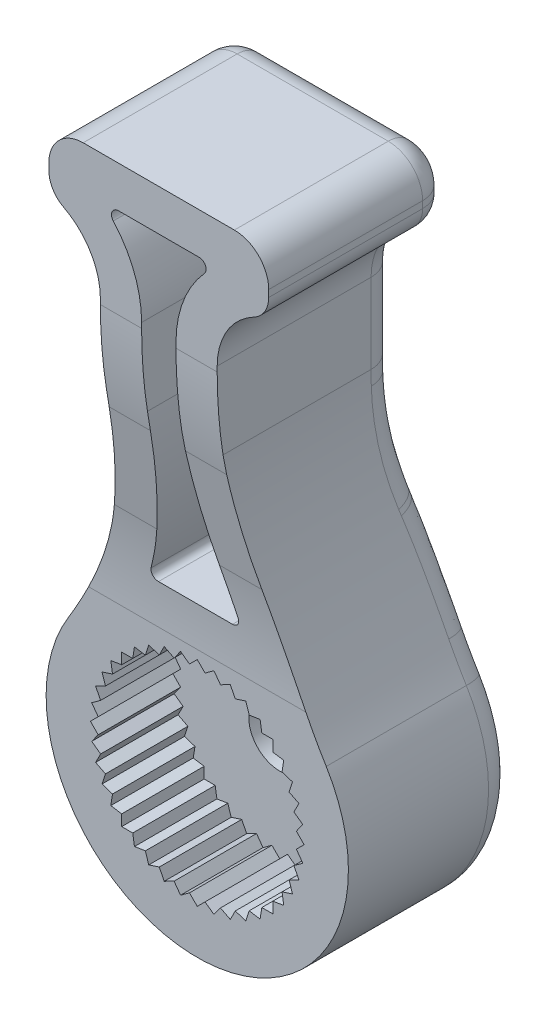
SolidWorks part; units mm, degrees
ref_plane "Plan de face" through (0, 0, 0) normal (0, 0, 1) x (1, 0, 0)
ref_plane "Plan de dessus" through (0, 0, 0) normal (0, 1, 0) x (1, 0, 0)
ref_plane "Plan de droite" through (0, 0, 0) normal (1, 0, 0) x (0, 0, -1)
sketch "Esquisse1" plane through (0, 0, 0) normal (0, 0, 1) x (1, 0, 0)
  line L0 (-5.5, 39) -> (5.5, 39)
  line L1 (0, 0) -> (0, 54.3296) construction
  line L2 (4.25, 29.8002) -> (4.25, 23.9883)
  line L3 (0, 0) -> (0, -12.9664) construction
  line L4 (-8, 36.5) -> (-8, 36)
  line L5 (8, 36.5) -> (8, 36)
  line L6 (-4.25, 29.8002) -> (-4.25, 23.9883)
  arc A0 (-9.3859, 5.7363) -> (9.3859, 5.7363) centre (0, 0) ccw
  arc A1 (5.5, 39) -> (8, 36.5) centre (5.5, 36.5) cw
  arc A2 (9.3859, 5.7363) -> (4.25, 23.9883) centre (39.25, 23.9883) cw
  arc A3 (-6.9286, 34.2286) -> (-4.25, 29.8002) centre (-9.25, 29.8002) cw
  arc A4 (6.9286, 34.2286) -> (8, 36) centre (6, 36) ccw
  arc A5 (6.9286, 34.2286) -> (4.25, 29.8002) centre (9.25, 29.8002) ccw
  arc A6 (-6.9286, 34.2286) -> (-8, 36) centre (-6, 36) cw
  arc A7 (-9.3859, 5.7363) -> (-4.25, 23.9883) centre (-39.25, 23.9883) ccw
  arc A8 (-5.5, 39) -> (-8, 36.5) centre (-5.5, 36.5) ccw
  point P12 (8, 39)
  point P13 (0, 39)
  point P15 (-8, 39)
  dimension "D1" = 22
  dimension "D7" = 2.5
  dimension "D8" = 4.7714
  dimension "D9" = 5
  dimension "D6" = 2
  dimension "D10" = 35
  dimension "D2" = 39
  dimension "D3" = 8.5
  dimension "D5" = 8
extrude "Boss.-Extru.1" add sketch "Esquisse1" along normal blind 15
sketch "Esquisse2" plane through (0, 0, 0) normal (1, 0, 0) x (0, 0, -1)
  line L0 (-1.8, 39) -> (-1.8, 22.8889)
  line L1 (-12.2, -12.1591) -> (-12.2, 8.4134)
  line L2 (0, -11) -> (0, 5.7363) construction
  line L3 (-15, 34.2286) -> (-15, 29.8002) construction
  line L4 (-15, 39) -> (0, 39) construction
  line L5 (-1.8, 39) -> (0, 39)
  line L6 (-0.9463, 15.206) -> (-0.8537, 14.794)
  line L7 (0, 5.7363) -> (0, 23.9883) construction
  line L8 (0, 5.7363) -> (0, 7.1111)
  line L9 (-15, 23.9883) -> (-15, 29.8002) construction
  line L10 (-15, 29.4275) -> (-15, 29.8002)
  line L11 (-15, 23.9883) -> (-15, 5.7363) construction
  line L12 (-12.8649, 15.2032) -> (-14.3351, 22.6376)
  line L13 (-15, 29.8002) -> (-17.0161, 29.8002)
  line L14 (-17.0161, 29.8002) -> (-17.0161, -12.1591)
  line L15 (-17.0161, -12.1591) -> (-12.2, -12.1591)
  line L16 (0, 39) -> (7.2396, 39)
  line L17 (7.2396, 39) -> (7.2396, 8.4134)
  line L18 (7.2396, 8.4134) -> (0, 5.7363)
  arc A0 (-0.8537, 14.794) -> (0, 7.1111) centre (-35, 7.1111) cw
  arc A1 (-1.8, 22.8889) -> (-0.9463, 15.206) centre (33.2, 22.8889) ccw
  arc A2 (-15, 29.4275) -> (-14.3351, 22.6376) centre (20, 29.4275) ccw
  arc A3 (-12.2, 8.4134) -> (-12.8649, 15.2032) centre (-47.2, 8.4134) ccw
  point P16 (0, 11)
  point P19 (-1.8, 19)
  point P27 (-15, 26)
  point P30 (-12.2, 11.8409)
  dimension "D5" = 35
  dimension "D8" = 35
  dimension "D1" = 12.2
  dimension "D2" = 13.2
  dimension "D3" = 20
  dimension "D4" = 11
  dimension "D6" = 24
  dimension "D7" = 13
extrude "Enlèv. mat.-Extru.1" cut sketch "Esquisse2" against normal mid plane 25
fillet "Congé1" radius 2 22 edges at (4.2543, 23.4385, 1.8) (4.25, 26.8942, 1.8) (4.9717, 32.3879, 1.8) (7.7113, 34.9649, 1.8) (8, 36.25, 1.8) (7.2678, 38.2678, 1.8) (0, 39, 1.8) (-7.2678, 38.2678, 1.8) (-8, 36.25, 1.8) (-7.7113, 34.9649, 1.8) (-4.9717, 32.3879, 1.8) (-4.25, 26.8942, 1.8) (-4.2543, 23.4385, 1.8) (4.4594, 20.165, 1.6938) (5.4239, 14.9998, 0.9) (-5.4239, 14.9998, 0.9) (8.9791, 6.4192, 0) (-8.9791, 6.4192, 0) (0, -11, 0)
sketch "Esquisse3" plane through (0, 0, 12.2) normal (0, 0, 1) x (1, 0, 0)
  line L0 (-4.5719, 6.2928) -> (-3.7792, 6.1673)
  line L1 (-5.5, -5.5) -> (-4.6964, -5.5)
  line L2 (-5.5, -5.5) -> (-5.5, -4.6973)
  line L3 (-5.5, 5.5) -> (-4.6975, 5.5)
  line L4 (5.5, -5.5) -> (5.5, -4.6966)
  line L5 (-5.5, -5.5) -> (5.5, 5.5) construction
  line L6 (-5.5, 5.5) -> (5.5, -5.5) construction
  line L7 (-6.2927, -4.5717) -> (-6.1671, -3.7789)
  line L8 (-6.2927, -4.5717) -> (-5.5, -4.6973)
  line L9 (4.5719, -6.2925) -> (4.6974, -5.5)
  line L10 (-3.5312, 6.9307) -> (-2.7679, 6.6827)
  line L11 (-6.9304, -3.5309) -> (-6.6823, -2.7675)
  line L12 (-6.9304, -3.5309) -> (-6.1671, -3.7789)
  line L13 (3.5313, -6.9301) -> (3.7792, -6.167)
  line L14 (-2.4035, 7.3979) -> (-1.6884, 7.0336)
  line L15 (-7.3974, -2.4031) -> (-7.0329, -1.6879)
  line L16 (-7.3974, -2.4031) -> (-6.6823, -2.7675)
  line L17 (2.4037, -7.397) -> (2.768, -6.6821)
  line L18 (-1.2166, 7.683) -> (-0.5673, 7.2113)
  line L19 (-7.6822, -1.2162) -> (-7.2104, -0.5668)
  line L20 (-7.6822, -1.2162) -> (-7.0329, -1.6879)
  line L21 (1.217, -7.6818) -> (1.6886, -7.0327)
  line L22 (0.0003, 7.7789) -> (0.5678, 7.2114)
  line L23 (-7.7779, 0.0007) -> (-7.2103, 0.5683)
  line L24 (-7.7779, 0.0007) -> (-7.2104, -0.5668)
  line L25 (0.0003, -7.7775) -> (0.5677, -7.2101)
  line L26 (1.2172, 7.6832) -> (1.6889, 7.0339)
  line L27 (-7.682, 1.2176) -> (-7.0326, 1.6894)
  line L28 (-7.682, 1.2176) -> (-7.2103, 0.5683)
  line L29 (-1.2164, -7.6816) -> (-0.5672, -7.21)
  line L30 (2.4041, 7.3984) -> (2.7685, 6.6833)
  line L31 (-7.3969, 2.4045) -> (-6.6817, 2.7689)
  line L32 (-7.3969, 2.4045) -> (-7.0326, 1.6894)
  line L33 (-2.403, -7.3966) -> (-1.6881, -7.0323)
  line L34 (3.5319, 6.9314) -> (3.7799, 6.1681)
  line L35 (-6.9297, 3.5322) -> (-6.1663, 3.7802)
  line L36 (-6.9297, 3.5322) -> (-6.6817, 2.7689)
  line L37 (-3.5305, -6.9295) -> (-2.7674, -6.6815)
  line L38 (4.5727, 6.2937) -> (4.6984, 5.5)
  line L39 (-6.2918, 4.5729) -> (-5.5, 4.6983)
  line L40 (-6.2918, 4.5729) -> (-6.1663, 3.7802)
  line L41 (-4.5711, -6.2917) -> (-3.7785, -6.1662)
  line L42 (0.001, 0) -> (0, 0) construction
  line L43 (0.001, 0) -> (0, 0.0002) construction
  line L61 (6.1672, 3.7795) -> (6.9305, 3.5315)
  line L63 (3.7799, 6.1681) -> (4.5727, 6.2937)
  line L64 (2.7685, 6.6833) -> (3.5319, 6.9314)
  line L66 (4.6984, 5.5) -> (5.5, 5.5)
  line L68 (5.5, 4.6976) -> (6.2927, 4.5721)
  line L69 (5.5, 4.6976) -> (5.5, 5.5)
  line L71 (6.6825, 2.7684) -> (7.3976, 2.404)
  line L77 (6.1672, 3.7795) -> (6.2927, 4.5721)
  line L78 (6.6825, 2.7684) -> (6.9305, 3.5315)
  line L79 (7.0333, 1.6891) -> (7.6826, 1.2174)
  line L80 (7.0333, 1.6891) -> (7.3976, 2.404)
  line L81 (7.211, 0.5682) -> (7.7785, 0.0007)
  line L82 (7.211, 0.5682) -> (7.6826, 1.2174)
  line L83 (7.2111, -0.5667) -> (7.6828, -1.216)
  line L84 (7.2111, -0.5667) -> (7.7785, 0.0007)
  line L85 (7.0337, -1.6876) -> (7.6828, -1.216)
  line L86 (7.0337, -1.6876) -> (7.398, -2.4027)
  line L87 (6.168, -3.7782) -> (6.2935, -4.5709)
  line L91 (6.168, -3.7782) -> (6.9311, -3.5303)
  line L92 (6.6831, -2.767) -> (6.9311, -3.5303)
  line L93 (6.6831, -2.767) -> (7.398, -2.4027)
  line L94 (5.5, -4.6966) -> (6.2935, -4.5709)
  line L105 (4.6974, -5.5) -> (5.5, -5.5)
  line L106 (3.7792, -6.167) -> (4.5719, -6.2925)
  line L107 (2.768, -6.6821) -> (3.5313, -6.9301)
  line L109 (1.6886, -7.0327) -> (2.4037, -7.397)
  line L111 (0.5677, -7.2101) -> (1.217, -7.6818)
  line L113 (-0.5672, -7.21) -> (0.0003, -7.7775)
  line L115 (-1.6881, -7.0323) -> (-1.2164, -7.6816)
  line L118 (-2.7674, -6.6815) -> (-2.403, -7.3966)
  line L119 (-3.7785, -6.1662) -> (-3.5305, -6.9295)
  line L121 (-4.6964, -5.5) -> (-4.5711, -6.2917)
  line L140 (-5.5, 4.6983) -> (-5.5, 5.5)
  line L141 (-4.6975, 5.5) -> (-4.5719, 6.2928)
  line L143 (-3.7792, 6.1673) -> (-3.5312, 6.9307)
  line L145 (-4.8072, 4.8072) -> (-4.8071, 4.8081)
  line L146 (-4.8079, 4.8079) -> (-4.8071, 4.8081)
  line L147 (-2.7679, 6.6827) -> (-2.4035, 7.3979)
  line L150 (-1.6884, 7.0336) -> (-1.2166, 7.683)
  line L151 (-0.5673, 7.2113) -> (0.0003, 7.7789)
  line L153 (0.5678, 7.2114) -> (1.2172, 7.6832)
  line L154 (1.6889, 7.0339) -> (2.4041, 7.3984)
  point P0 (0, 0)
  point P6 (0, 0.0002)
  point P13 (0, 0.0003)
  point P18 (0.0001, 0.0005)
  point P23 (0.0002, 0.0006)
  point P28 (0.0003, 0.0007)
  point P33 (0.0004, 0.0008)
  point P38 (0.0005, 0.0009)
  point P43 (0.0007, 0.001)
  point P48 (0.0008, 0.001)
  dimension "D1" = 11
  dimension "D2" = 11
  dimension "D3" = 10
extrude "Enlèv. mat.-Extru.2" cut sketch "Esquisse3" against normal blind 6 contours L154 L26 L153 L22 L151 L18 L150 L14 L147 L10 L143 L0 L141 L3 L140 L39 L40 L35 L36 L31 L32 L27 L28 L23 L24 L19 L20 L15 L16 L11 L12 L7 L8 L2 L1 L121 L41 L119 L37 L118 L33 L115 L29 L113 L25 L111 L21 L109 L17 L107 L13
sketch "Esquisse4" plane through (0, 0, 15) normal (0, 0, 1) x (1, 0, 0)
  line L12 (-1.6937, 32.4275) -> (1.6937, 32.4275)
  line L13 (4.1941, 36) -> (-4.1941, 36)
  line L15 (2.9443, 36) -> (-2.9443, 36)
  line L18 (1.25, 25.6376) -> (1.25, 26.4275)
  line L19 (1.25, 26.4275) -> (-1.25, 26.4275)
  line L20 (-1.25, 26.4275) -> (-1.25, 25.6376)
  line L21 (-1.25, 25.6376) -> (1.25, 25.6376)
  line L22 (1.25, 23.9883) -> (1.25, 29.8002)
  line L24 (-1.25, 29.8002) -> (-1.25, 23.9883)
  line L26 (1.4999, 19.6376) -> (-1.4999, 19.6376)
  line L27 (-1.6929, 18.2032) -> (1.6929, 18.2032)
  line L32 (3.1237, 12.2032) -> (-3.1237, 12.2032)
  line L33 (-3.3909, 11.4134) -> (3.3909, 11.4134)
  line L35 (-2.6926, 11.4134) -> (2.6926, 11.4134)
  arc A0 (3.3152, 35.1647) -> (2.9443, 36) centre (2.9443, 35.5) ccw
  arc A1 (-3.3152, 35.1647) -> (-2.9443, 36) centre (-2.9443, 35.5) cw
  arc A2 (2.6926, 11.4134) -> (3.1673, 12.0702) centre (2.6926, 11.9134) ccw
  arc A3 (-3.1673, 12.0702) -> (-2.6926, 11.4134) centre (-2.6926, 11.9134) ccw
  arc A12 (-1.6937, 32.4275) -> (-4.1941, 36) centre (-9.25, 29.8002) ccw
  arc A13 (4.1941, 36) -> (1.6937, 32.4275) centre (9.25, 29.8002) ccw
  arc A14 (-1.25, 29.8002) -> (-3.3152, 35.1647) centre (-9.25, 29.8002) ccw
  arc A15 (3.3152, 35.1647) -> (1.25, 29.8002) centre (9.25, 29.8002) ccw
  arc A16 (-1.6929, 18.2032) -> (-1.4999, 19.6376) centre (-39.25, 23.9883) ccw
  arc A17 (1.4999, 19.6376) -> (1.6929, 18.2032) centre (39.25, 23.9883) ccw
  arc A18 (-3.1237, 12.2032) -> (-1.25, 23.9883) centre (-39.25, 23.9883) ccw
  arc A19 (1.25, 23.9883) -> (3.1237, 12.2032) centre (39.25, 23.9883) ccw
  arc A22 (-3.3909, 11.4134) -> (-3.1237, 12.2032) centre (-39.25, 23.9883) ccw
  arc A23 (3.1237, 12.2032) -> (3.3909, 11.4134) centre (39.25, 23.9883) ccw
  arc A24 (-3.1673, 12.0702) -> (-3.1237, 12.2032) centre (-39.25, 23.9883) ccw
  arc A25 (3.1237, 12.2032) -> (3.1673, 12.0702) centre (39.25, 23.9883) ccw
  dimension "D5" = 0.5
  dimension "D6" = 0.5
  dimension "D1" = 3
  dimension "D2" = 3
  dimension "D3" = 3
  dimension "D4" = 3
extrude "Enlèv. mat.-Extru.3" cut sketch "Esquisse4" against normal blind 9.5
hole_wizard "Fraisage pour vis à tête fraisée M41" positions "Esquisse6" profile "Esquisse5" countersink size "M4" standard "ISO" end condition through all
sketch "Esquisse6" plane through (0, 0, 0) normal (0, 0, -1) x (-1, 0, 0)
  point P1 (0, 0)
sketch "Esquisse5" plane through (0, 0, 0) normal (1, 0, 0) x (0, 1, 0)
  line L0 (0, 0) -> (0, 15)
  line L1 (0, 15) -> (2.25, 15)
  line L2 (2.25, 15) -> (2.25, 1.45)
  line L3 (2.25, 1.45) -> (3.7, 0)
  line L5 (3.7, 0) -> (0, 0)
  line L6 (-2.25, 1.45) -> (-3.7, 0) construction
  line L11 (0, -6.35) -> (0, 107.95) construction
  dimension "Diamètre du perçage jusqu'au prochain" = 4.5
  dimension "Profondeur du perçage jusqu'au prochain" = 15
  dimension "Diamètre du fraisage entrant" = 7.4
  dimension "Angle du fraisage entrant" = 90
